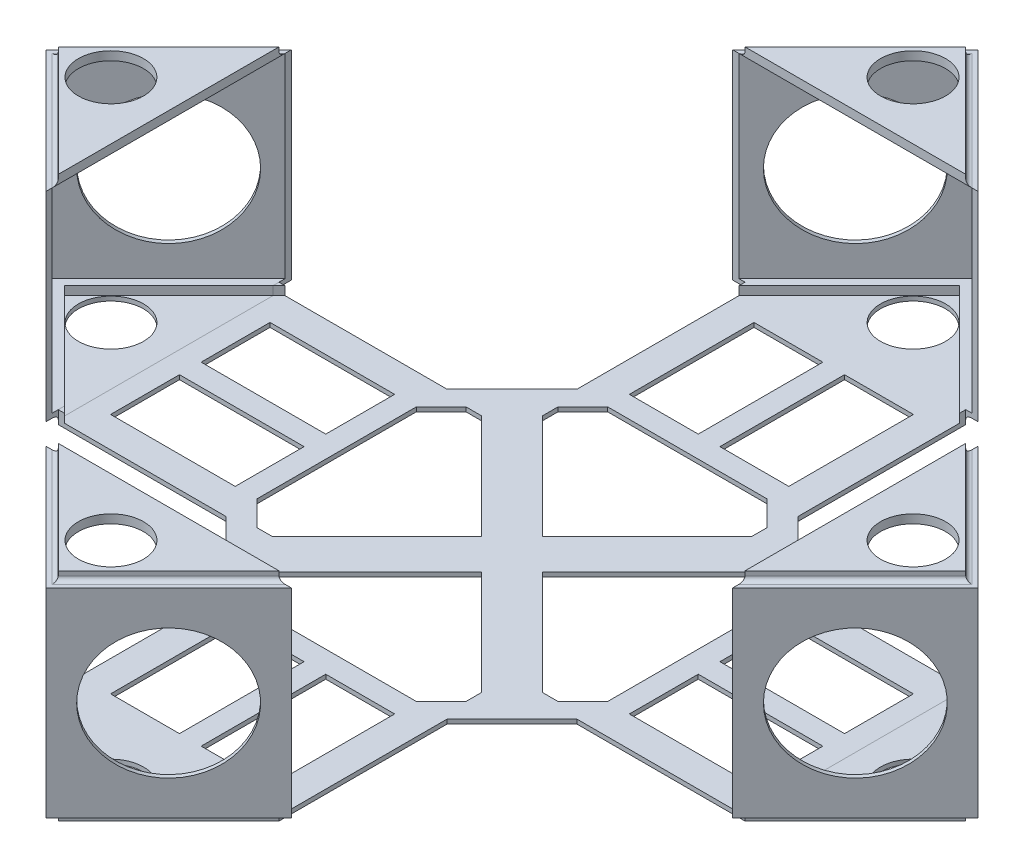
SolidWorks part; units mm, degrees
material "ABS"
ref_plane "前基準面" through (0, 0, 0) normal (0, 0, 1) x (1, 0, 0)
ref_plane "上基準面" through (0, 0, 0) normal (0, 1, 0) x (1, 0, 0)
ref_plane "右基準面" through (0, 0, 0) normal (1, 0, 0) x (0, 0, -1)
sketch "草圖1" plane through (0, 0, 0) normal (0, 1, 0) x (1, 0, 0)
  line L0 (-214.9605, 0) -> (0, -214.9605) construction
  line L1 (-214.9605, 0) -> (0, 214.9605) construction
  line L2 (0, -214.9605) -> (214.9605, 0) construction
  line L3 (0, 214.9605) -> (214.9605, 0) construction
  line L4 (-214.9605, 0) -> (214.9605, 0) construction
  line L5 (0, -214.9605) -> (0, 214.9605) construction
  line L6 (-158.3919, 56.5685) -> (-214.9605, 0)
  line L7 (-214.9605, 0) -> (-158.3919, -56.5685)
  line L8 (-158.3919, -56.5685) -> (-158.3919, 56.5685)
  line L9 (158.3919, 56.5685) -> (214.9605, 0)
  line L10 (214.9605, 0) -> (158.3919, -56.5685)
  line L11 (158.3919, -56.5685) -> (158.3919, 56.5685)
  line L12 (-185, 0) -> (185, 0) construction
  circle A0 centre (-185, 0) radius 15
  circle A1 centre (185, 0) radius 15
  point P1 (0, 0)
  point P14 (0, 0)
  dimension "D4" = 30
  dimension "D1" = 304
  dimension "D2" = 80
  dimension "D3" = 370
extrude "填料-伸長1" add sketch "草圖1" along normal mid plane 100
sketch "草圖2" plane through (0, 50, 0) normal (0, 1, 0) x (1, 0, 0)
  line L0 (-214.9605, 0) -> (-158.3919, -56.5685)
  line L1 (-158.3919, -56.5685) -> (-155.5635, -53.7401)
  line L2 (-155.5635, -53.7401) -> (-209.3036, 0)
  line L3 (-209.3036, 0) -> (-155.5635, 53.7401)
  line L4 (-155.5635, 53.7401) -> (-158.3919, 56.5685)
  line L5 (-158.3919, 56.5685) -> (-214.9605, 0)
  line L6 (214.9605, 0) -> (158.3919, -56.5685)
  line L7 (158.3919, -56.5685) -> (155.5635, -53.7401)
  line L8 (155.5635, -53.7401) -> (209.3036, 0)
  line L9 (209.3036, 0) -> (155.5635, 53.7401)
  line L10 (155.5635, 53.7401) -> (158.3919, 56.5685)
  line L11 (158.3919, 56.5685) -> (214.9605, 0)
  dimension "D1" = 4
extrude "除料-伸長1" cut sketch "草圖2" against normal blind 4
mirror "鏡射2" about plane through (0, 0, 0) normal (0, 1, 0) of "除料-伸長1"
fillet "圓角1" radius 2 4 edges at (-183.8478, -46, 25.4558) (-183.8478, -46, -25.4558) (-183.8478, 46, -25.4558) (-183.8478, 46, 25.4558)
fillet "圓角2" radius 2 4 edges at (183.8478, 46, 25.4558) (183.8478, 46, -25.4558) (183.8478, -46, -25.4558) (183.8478, -46, 25.4558)
sketch "草圖3" plane through (0, 0, 0) normal (0, 0, 1) x (1, 0, 0)
  line L0 (0, 0) -> (0, 42.2021)
pattern_circular "環狀複製排列1" count 2 every 90 about axis through (0, 0, 0) along (0, 1, 0) of bodies 105
pattern_circular "環狀複製排列2" count 2 every 90 about axis through (0, 0, 0) along (0, 1, 0) of bodies 105
sketch "草圖4" plane through (0, -50, 0) normal (0, -1, 0) x (1, 0, 0)
  line L0 (-50.9117, 158.3919) -> (-50.9117, 80.9117)
  line L1 (-50.9117, -158.3919) -> (50.9117, -158.3919)
  line L2 (50.9117, -158.3919) -> (50.9117, -80.9117)
  line L3 (50.9117, 158.3919) -> (0, 209.3036) construction
  line L4 (50.9117, 158.3919) -> (-50.9117, 158.3919) construction
  line L5 (50.9117, 158.3919) -> (-50.9117, 158.3919)
  line L6 (-80.9117, 50.9117) -> (-158.3919, 50.9117)
  line L7 (158.3919, 50.9117) -> (80.9117, 50.9117)
  line L8 (158.3919, 50.9117) -> (158.3919, -50.9117)
  line L9 (158.3919, -50.9117) -> (80.9117, -50.9117)
  line L10 (-158.3919, 50.9117) -> (-158.3919, -50.9117)
  line L11 (50.9117, 80.9117) -> (50.9117, 158.3919)
  line L12 (-80.9117, -50.9117) -> (-158.3919, -50.9117)
  line L13 (-50.9117, -80.9117) -> (-50.9117, -158.3919)
  line L14 (80.9117, 50.9117) -> (50.9117, 80.9117)
  line L15 (-50.9117, 80.9117) -> (-80.9117, 50.9117)
  line L16 (-50.9117, -80.9117) -> (-80.9117, -50.9117)
  line L17 (50.9117, -80.9117) -> (80.9117, -50.9117)
  line L18 (65.9117, 65.9117) -> (-65.9117, -65.9117) construction
  line L19 (65.9117, -65.9117) -> (-65.9117, 65.9117) construction
  line L20 (48.234, 62.3762) -> (0, 14.1421)
  line L21 (0, 14.1421) -> (-48.234, 62.3762)
  line L22 (-36.7696, 80.9117) -> (36.7696, 80.9117)
  line L23 (48.234, 69.4472) -> (36.7696, 80.9117)
  line L24 (-48.234, 69.4472) -> (-36.7696, 80.9117)
  line L25 (48.234, 62.3762) -> (48.234, 69.4472)
  line L26 (-48.234, 62.3762) -> (-48.234, 69.4472)
  line L27 (80.9127, 36.7706) -> (80.9127, -36.7686)
  line L28 (69.4482, -48.233) -> (80.9127, -36.7686)
  line L29 (62.3772, -48.233) -> (69.4482, -48.233)
  line L30 (62.3772, -48.233) -> (14.1431, 0.001)
  line L31 (14.1431, 0.001) -> (62.3772, 48.235)
  line L32 (62.3772, 48.235) -> (69.4482, 48.235)
  line L33 (69.4482, 48.235) -> (80.9127, 36.7706)
  line L34 (36.7716, -80.9117) -> (-36.7676, -80.9117)
  line L35 (-48.232, -69.4472) -> (-36.7676, -80.9117)
  line L36 (-48.232, -62.3762) -> (-48.232, -69.4472)
  line L37 (-48.232, -62.3762) -> (0.002, -14.1421)
  line L38 (0.002, -14.1421) -> (48.236, -62.3762)
  line L39 (48.236, -62.3762) -> (48.236, -69.4472)
  line L40 (48.236, -69.4472) -> (36.7716, -80.9117)
  line L41 (-80.9107, -36.7706) -> (-80.9107, 36.7686)
  line L42 (-69.4462, 48.233) -> (-80.9107, 36.7686)
  line L43 (-62.3752, 48.233) -> (-69.4462, 48.233)
  line L44 (-62.3752, 48.233) -> (-14.1411, -0.001)
  line L45 (-14.1411, -0.001) -> (-62.3752, -48.235)
  line L46 (-62.3752, -48.235) -> (-69.4462, -48.235)
  line L47 (-69.4462, -48.235) -> (-80.9107, -36.7706)
  line L48 (90.9117, -36.7696) -> (90.9117, -5)
  line L49 (36.7696, 90.9117) -> (5, 90.9117)
  line L50 (36.7696, 90.9117) -> (36.7696, 148.3919)
  line L51 (36.7696, 148.3919) -> (5, 148.3919)
  line L52 (5, 90.9117) -> (5, 148.3919)
  line L53 (-36.7696, 90.9117) -> (-5, 90.9117)
  line L54 (-36.7696, 90.9117) -> (-36.7696, 148.3919)
  line L55 (-36.7696, 148.3919) -> (-5, 148.3919)
  line L56 (-5, 90.9117) -> (-5, 148.3919)
  line L57 (90.9117, -5) -> (148.3919, -5)
  line L58 (148.3919, -36.7696) -> (148.3919, -5)
  line L59 (90.9117, -36.7696) -> (148.3919, -36.7696)
  line L60 (90.9117, 36.7696) -> (90.9117, 5)
  line L61 (90.9117, 36.7696) -> (148.3919, 36.7696)
  line L62 (148.3919, 36.7696) -> (148.3919, 5)
  line L63 (90.9117, 5) -> (148.3919, 5)
  line L64 (-36.7696, -90.9117) -> (-5, -90.9117)
  line L65 (-5, -90.9117) -> (-5, -148.3919)
  line L66 (-36.7696, -148.3919) -> (-5, -148.3919)
  line L67 (-36.7696, -90.9117) -> (-36.7696, -148.3919)
  line L68 (36.7696, -90.9117) -> (5, -90.9117)
  line L69 (36.7696, -90.9117) -> (36.7696, -148.3919)
  line L70 (36.7696, -148.3919) -> (5, -148.3919)
  line L71 (5, -90.9117) -> (5, -148.3919)
  line L72 (-90.9117, 36.7696) -> (-90.9117, 5)
  line L73 (-90.9117, 5) -> (-148.3919, 5)
  line L74 (-148.3919, 36.7696) -> (-148.3919, 5)
  line L75 (-90.9117, 36.7696) -> (-148.3919, 36.7696)
  line L76 (-90.9117, -36.7696) -> (-90.9117, -5)
  line L77 (-90.9117, -36.7696) -> (-148.3919, -36.7696)
  line L78 (-148.3919, -36.7696) -> (-148.3919, -5)
  line L79 (-90.9117, -5) -> (-148.3919, -5)
  point P17 (50.9117, 50.9117)
  point P18 (-50.9117, 50.9117)
  point P19 (50.9117, -50.9117)
  point P20 (-50.9117, -50.9117)
  point P36 (-51.7696, 65.9117)
  point P41 (51.7696, 65.9117)
  point P45 (0, 0)
  point P67 (0.001, 0)
  point P100 (0, 0)
  dimension "D1" = 10
  dimension "D2" = 10
  dimension "D7" = 10
  dimension "D9" = 10
  dimension "D10" = 10
  dimension "D13" = 10
  dimension "D8" = 4
  dimension "D14" = 4
extrude "填料-伸長2" add sketch "草圖4" against normal blind 6
sketch "草圖5" plane through (0, -44, 0) normal (0, 1, 0) x (1, 0, 0)
  line L0 (212.132, 0) -> (0, 212.132)
  line L1 (212.132, 0) -> (0, -212.132)
  line L2 (0, 212.132) -> (-212.132, 0)
  line L3 (0, -212.132) -> (-212.132, 0)
  line L4 (212.132, 0) -> (-212.132, 0) construction
  line L5 (0, 212.132) -> (0, -212.132) construction
  line L6 (-50.9117, 158.3919) -> (0, 209.3036) construction
  line L8 (0, -214.9605) -> (56.5685, -158.3919) construction
  point P1 (0, 0)
  point P3 (0, -192.6396)
  point P9 (0, -211.2132)
  dimension "D1" = 2
extrude "除料-伸長2" cut sketch "草圖5" along normal up to surface (90 mm away) up to face at (0, 46, 176.7767)
sketch "草圖7" plane through (-107.4802, 0, -107.4802) normal (-0.7071, 0, -0.7071) x (-0.7071, 0, 0.7071)
  line L0 (-72, 46) -> (-152, -46) construction
  line L1 (152, 46) -> (72, -46) construction
  line L2 (72, 46) -> (72, -46) construction
  line L3 (72, -46) -> (152, -46) construction
  circle A0 centre (-112, 0) radius 30
  circle A1 centre (112, 0) radius 30
  dimension "D1" = 60
extrude "除料-伸長3" cut sketch "草圖7" against normal through all
pattern_circular "環狀複製排列3" count 2 every 90 about axis through (0, 0, 0) along (0, 1, 0) of "除料-伸長3"
sketch "草圖8" plane through (0, -44, 0) normal (0, 1, 0) x (1, 0, 0)
  line L0 (206.4752, 0) -> (0, 206.4752)
  line L1 (206.4752, 0) -> (0, -206.4752)
  line L2 (0, 206.4752) -> (-206.4752, 0)
  line L3 (0, -206.4752) -> (-206.4752, 0)
  line L4 (206.4752, 0) -> (-206.4752, 0) construction
  line L5 (0, 206.4752) -> (0, -206.4752) construction
  line L6 (-50.9117, 158.3919) -> (0, 209.3036) construction
  point P1 (0, 0)
  dimension "D1" = 2
extrude "除料-伸長4" cut sketch "草圖8" against normal blind 4
